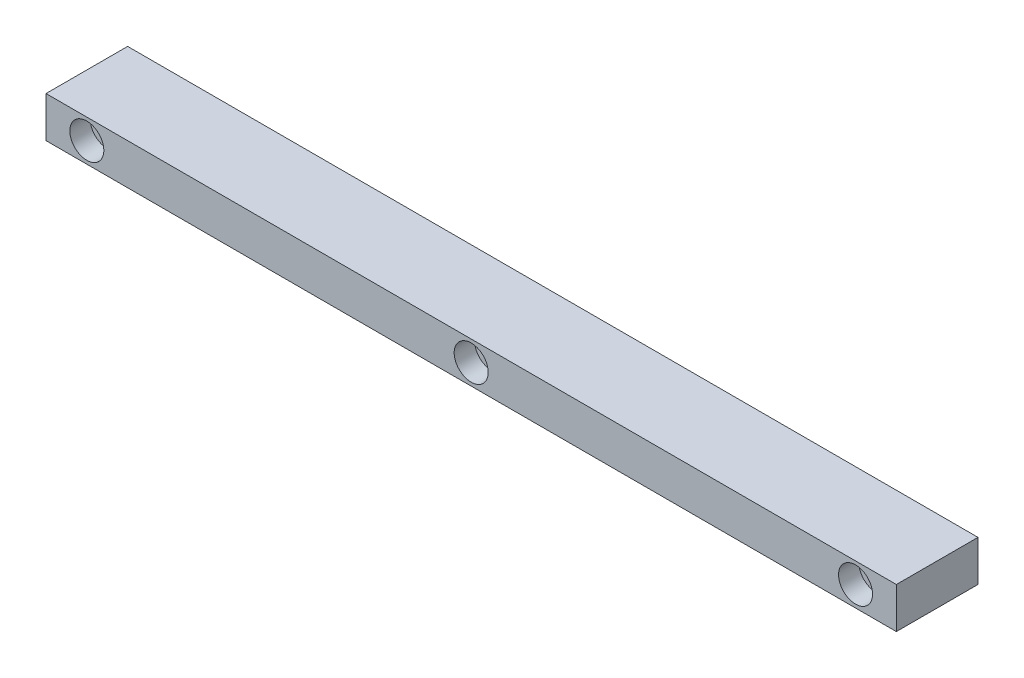
SolidWorks part; units mm, degrees
material "Sapin"
ref_plane "Plan de face" through (0, 0, 0) normal (0, 0, 1) x (1, 0, 0)
ref_plane "Plan de dessus" through (0, 0, 0) normal (0, 1, 0) x (1, 0, 0)
ref_plane "Plan de droite" through (0, 0, 0) normal (1, 0, 0) x (0, 0, -1)
sketch "Esquisse1" plane through (0, 0, 0) normal (0, 0, 1) x (1, 0, 0)
  line L1 (-250, -12) -> (250, -12)
  line L2 (-250, -12) -> (-250, 12)
  line L3 (-250, 12) -> (250, 12)
  line L4 (250, -12) -> (250, 12)
  line L5 (-250, -12) -> (250, 12) construction
  line L6 (-250, 12) -> (250, -12) construction
  point P0 (0, 0)
  dimension "D1" = 500
  dimension "D2" = 24
extrude "Boss.-Extru.1" add sketch "Esquisse1" along normal blind 48
sketch "Esquisse2" plane through (0, 0, 48) normal (0, 0, 1) x (1, 0, 0)
  line L0 (-250, 12) -> (-250, -12) construction
  line L1 (250, -12) -> (250, 12) construction
  circle A0 centre (-226, 0) radius 4
  circle A1 centre (0, 0) radius 4
  circle A2 centre (226, 0) radius 4
  dimension "D3" = 8
  dimension "D1" = 24
  dimension "D2" = 24
extrude "Enlèv. mat.-Extru.1" cut sketch "Esquisse2" against normal through all
sketch "Esquisse3" plane through (0, 0, 48) normal (0, 0, 1) x (1, 0, 0)
  circle A0 centre (-226, 0) radius 10
  circle A1 centre (0, 0) radius 10
  circle A2 centre (226, 0) radius 10
  dimension "D1" = 20
extrude "Enlèv. mat.-Extru.2" cut sketch "Esquisse3" against normal blind 12
sketch "Esquisse4" plane through (0, 0, 0) normal (0, 0, -1) x (-1, 0, 0)
  circle A0 centre (-226, 0) radius 7
  circle A1 centre (0, 0) radius 7
  circle A2 centre (226, 0) radius 7
  dimension "D1" = 14
extrude "Enlèv. mat.-Extru.3" cut sketch "Esquisse4" against normal blind 12
